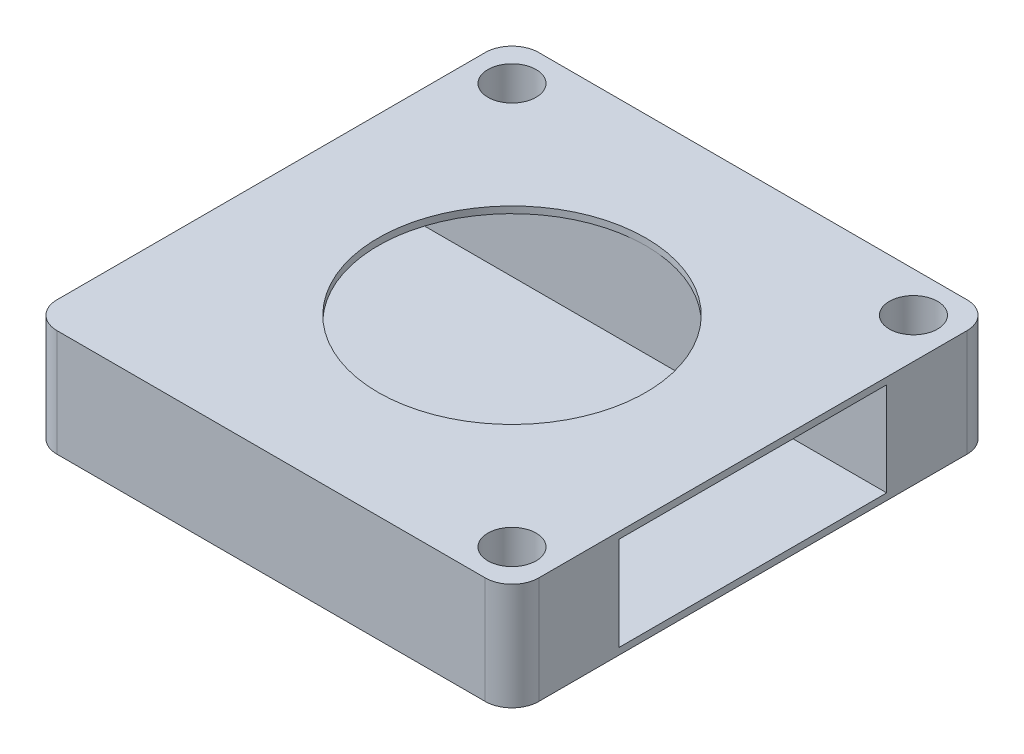
SolidWorks part; units mm, degrees
ref_plane "Front Plane" through (0, 0, 0) normal (0, 0, 1) x (1, 0, 0)
ref_plane "Top Plane" through (0, 0, 0) normal (0, 1, 0) x (1, 0, 0)
ref_plane "Right Plane" through (0, 0, 0) normal (1, 0, 0) x (0, 0, -1)
sketch "Sketch3" plane through (0, 0, 0) normal (0, 1, 0) x (1, 0, 0)
  line L1 (-8, -9) -> (8, -9)
  line L2 (-9, -8) -> (-9, 8)
  line L3 (-8, 9) -> (8, 9)
  line L4 (9, -8) -> (9, 8)
  line L5 (-9, -9) -> (9, 9) construction
  line L6 (-9, 9) -> (9, -9) construction
  arc A0 (9, 8) -> (8, 9) centre (8, 8) ccw
  arc A1 (8, -9) -> (9, -8) centre (8, -8) ccw
  arc A2 (-9, -8) -> (-8, -9) centre (-8, -8) ccw
  arc A3 (-8, 9) -> (-9, 8) centre (-8, 8) ccw
  point P0 (0, 0)
  point P21 (0, 0)
  dimension "D3" = 2
  dimension "D1" = 18
  dimension "D2" = 18
  dimension "D4" = 4
extrude "Boss-Extrude1" add sketch "Sketch3" along normal blind 4
sketch "Sketch4" plane through (0, 4, 0) normal (0, 1, 0) x (1, 0, 0)
  line L0 (-9, 0) -> (9, 0) construction
  line L1 (-9, 8) -> (-9, -8) construction
  line L2 (9, -8) -> (9, 8) construction
  line L3 (0, 0) -> (0, 7.3205) construction
  line L8 (-7.5, -7.5) -> (7.5, 7.5) construction
  line L9 (-7.5, 7.5) -> (7.5, -7.5) construction
  circle A1 centre (7.5, -7.5) radius 0.9
  circle A4 centre (7.5, 7.5) radius 0.9
  circle A5 centre (-7.5, 7.5) radius 0.9
  point P6 (0, 0)
  point P22 (0, 0)
  dimension "D1" = 15
  dimension "D2" = 15
extrude "Cut-Extrude1" cut sketch "Sketch4" against normal up to next
sketch "Sketch5" plane through (0, 4, 0) normal (0, 1, 0) x (1, 0, 0)
  line L0 (-9, 9) -> (9, -9) construction
  circle A0 centre (0, 0) radius 5
  point P0 (0, 0)
  dimension "D1" = 10
extrude "Cut-Extrude2" cut sketch "Sketch5" against normal offset from surface (3.75 mm away) 0.25 up to face at (-7.5, 0, -6.6)
sketch "Sketch6" plane through (9, 0, 0) normal (1, 0, 0) x (0, 0, -1)
  line L0 (-8, 0) -> (8, 0) construction
  line L1 (-5, 0.25) -> (5, 0.25)
  line L2 (-5, 0.25) -> (-5, 3.75)
  line L3 (-5, 3.75) -> (5, 3.75)
  line L4 (5, 0.25) -> (5, 3.75)
  line L5 (-5, 0.25) -> (5, 3.75) construction
  line L6 (-5, 3.75) -> (5, 0.25) construction
  point P0 (0, 2)
  dimension "D1" = 0.25
  dimension "D2" = 10
extrude "Cut-Extrude3" cut sketch "Sketch6" against normal blind 17.5
